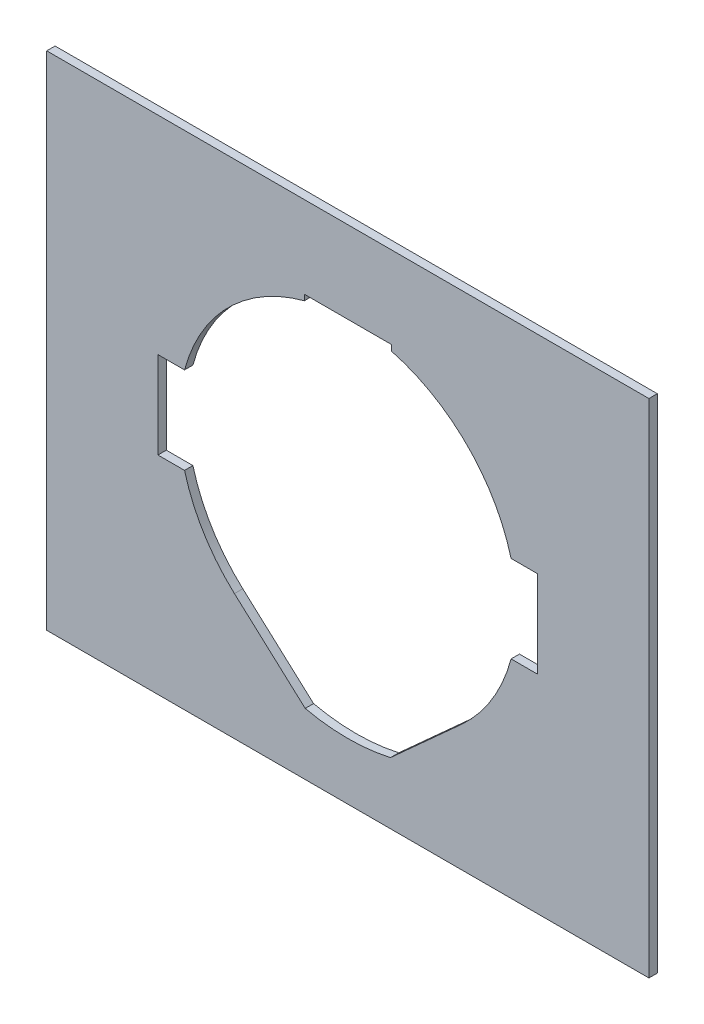
SolidWorks part; units mm, degrees
material "Ethylene-Vinyl Acetate Foam"
ref_plane "前基準面" through (0, 0, 0) normal (0, 0, 1) x (1, 0, 0)
ref_plane "上基準面" through (0, 0, 0) normal (0, 1, 0) x (1, 0, 0)
ref_plane "右基準面" through (0, 0, 0) normal (1, 0, 0) x (0, 0, -1)
sketch "草圖1" plane through (0, 0, 0) normal (0, 0, 1) x (1, 0, 0)
  line L1 (-360, 300) -> (360, 300)
  line L2 (-360, 300) -> (-360, -300)
  line L3 (-360, -300) -> (360, -300)
  line L4 (360, 300) -> (360, -300)
  line L5 (-360, 300) -> (360, -300) construction
  line L6 (-360, -300) -> (360, 300) construction
  point P0 (0, 0)
  dimension "D1" = 720
  dimension "D2" = 600
extrude "填料-伸長1" add sketch "草圖1" along normal blind 10
sketch "草圖2" plane through (0, 0, 10) normal (0, 0, 1) x (1, 0, 0)
  line L0 (225, -50) -> (225, 50) construction
  line L1 (225, 50) -> (125, 50) construction
  line L2 (125, 50) -> (125, -50) construction
  line L3 (125, -50) -> (225, -50) construction
  line L4 (50, 100) -> (50, 200) construction
  line L5 (50, 200) -> (-50, 200) construction
  line L6 (-50, 200) -> (-50, 100) construction
  line L7 (-50, 100) -> (50, 100) construction
  line L8 (-125, -50) -> (-125, 50) construction
  line L9 (-125, 50) -> (-225, 50) construction
  line L10 (-225, 50) -> (-225, -50) construction
  line L11 (-225, -50) -> (-125, -50) construction
  line L12 (50, -224.4994) -> (134.2088, -148.2835) construction
  line L13 (-50, -224.4994) -> (-134.2088, -148.2835) construction
  line L14 (225, -50) -> (225, 50)
  line L15 (225, 50) -> (125, 50)
  line L16 (125, 50) -> (125, -50)
  line L17 (125, -50) -> (225, -50)
  line L18 (50, 100) -> (50, 200)
  line L19 (50, 200) -> (-50, 200)
  line L20 (-50, 200) -> (-50, 100)
  line L21 (-50, 100) -> (50, 100)
  line L22 (-125, -50) -> (-125, 50)
  line L23 (-125, 50) -> (-225, 50)
  line L24 (-225, 50) -> (-225, -50)
  line L25 (-225, -50) -> (-125, -50)
  line L26 (50, -224.4994) -> (134.2088, -148.2835)
  line L27 (-50, -224.4994) -> (-134.2088, -148.2835)
  line L28 (-50.9513, -226.336) -> (-135.5509, -149.7663)
  line L29 (50.9513, -226.336) -> (135.5509, -149.7663)
  line L30 (-227, 52) -> (-227, -52)
  line L31 (-227, -52) -> (-123, -52)
  line L32 (-123, -52) -> (-123, 52)
  line L33 (-123, 52) -> (-227, 52)
  line L34 (52, 202) -> (-52, 202)
  line L35 (-52, 202) -> (-52, 98)
  line L36 (-52, 98) -> (52, 98)
  line L37 (52, 98) -> (52, 202)
  line L38 (227, -52) -> (227, 52)
  line L39 (227, 52) -> (123, 52)
  line L40 (123, 52) -> (123, -52)
  line L41 (123, -52) -> (227, -52)
  arc A0 (-50, -224.4994) -> (50, -224.4994) centre (0, 0) ccw construction
  arc A1 (134.2088, -148.2835) -> (-134.2088, -148.2835) centre (0, 0) ccw construction
  arc A2 (-50, -224.4994) -> (50, -224.4994) centre (0, 0) ccw
  arc A3 (134.2088, -148.2835) -> (-134.2088, -148.2835) centre (0, 0) ccw
  arc A4 (135.5509, -149.7663) -> (-135.5509, -149.7663) centre (0, 0) ccw
  arc A5 (-50.9513, -226.336) -> (50.9513, -226.336) centre (0, 0) ccw
  dimension "D1" = 2
  dimension "D2" = 2
extrude "除料-伸長2" cut sketch "草圖2" against normal through all contours A4 L33 L30 L31 L25 L24 L23 | A4 L23 L24 L25 | L23 A3 L25 L22 | L23 A4 L25 A3 | L33 A4 L23 A3 | L35 A4 L33 A3 | L39 A3 L37 L36 L35 L33 L32 L31 L27 A2 L26 L41 L40 | L33 A3 L23 L22 L25 L31 L32 | L18 A3 L20 L21 | L37 A3 L18 L21 L20 L35 L36 | A4 L19 L20 | A4 L34 L35 L20 L19 | L20 A4 L35 A3 | L19 A4 L20 A3 | L19 A4 | A4 L37 L34 L19 L18 | L18 A4 L19 A3 | A4 L18 L19 | L37 A4 L18 A3 | L39 A4 L37 A3 | L17 A3 L15 L16 | L15 A3 L39 L40 L41 L17 L16 | A4 L17 L14 L15 | L17 A4 L15 A3 | L15 A4 L39 A3 | A4 L15 L14 L17 L41 L38 L39 | L41 A4 L17 A3 | L28 A5 L29 A4 L41 A3 L26 A2 L27 L31 | L25 A4 L31 A3
